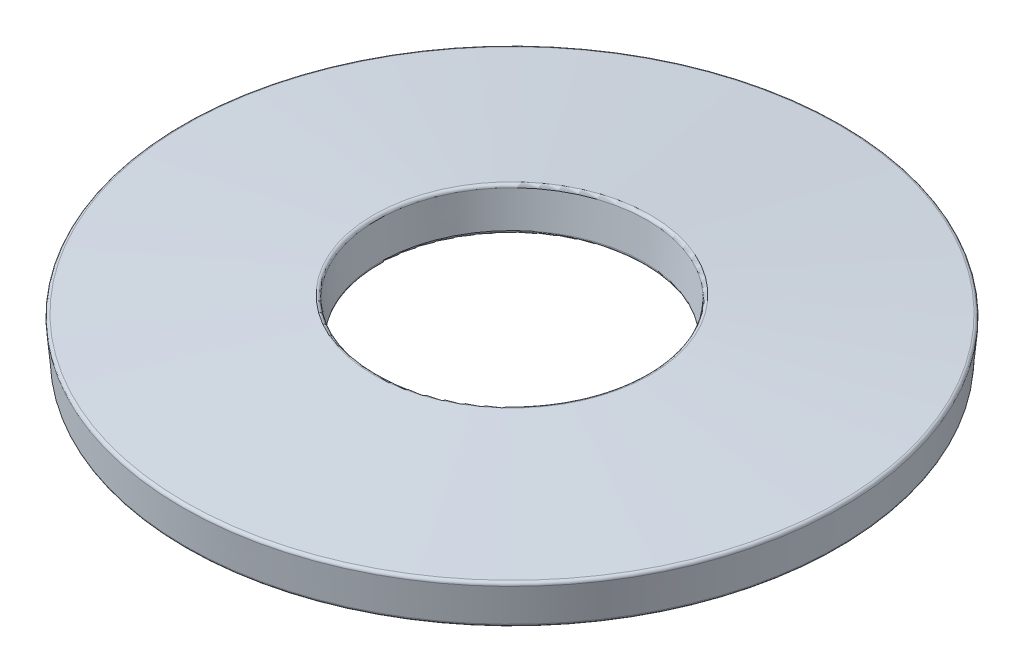
SolidWorks part; units mm, degrees
ref_plane "Front Plane" through (0, 0, 0) normal (0, 0, 1) x (1, 0, 0)
ref_plane "Top Plane" through (0, 0, 0) normal (0, 1, 0) x (1, 0, 0)
ref_plane "Right Plane" through (0, 0, 0) normal (1, 0, 0) x (0, 0, -1)
sketch "Sketch1" plane through (0, 0, 0) normal (0, 0, 1) x (1, 0, 0)
  line L0 (0, 0.35) -> (0, -0.35) construction
  line L1 (1.6427, 0.35) -> (4, 0.1482)
  line L2 (4, 0.1482) -> (3.9573, -0.35)
  line L3 (3.9573, -0.35) -> (1.6, -0.1482)
  line L4 (1.6, -0.1482) -> (1.6427, 0.35)
  line L5 (3.9573, -0.35) -> (1.5919, -0.2999) construction
  line L6 (1.5919, -0.2999) -> (1.6025, 0.2) construction
  line L7 (1.6025, 0.2) -> (3.9679, 0.1499) construction
  line L8 (3.9679, 0.1499) -> (3.9573, -0.35) construction
  line L9 (-3.9679, 0.1499) -> (-3.9573, -0.35) construction
  line L10 (-1.6025, 0.2) -> (-3.9679, 0.1499) construction
  line L11 (-1.5919, -0.2999) -> (-1.6025, 0.2) construction
  line L12 (-3.9573, -0.35) -> (-1.5919, -0.2999) construction
  point P11 (1.6025, 0.2)
  dimension "Thickness" = 0.5
  dimension "OD" = 8
  dimension "ID" = 3.2
  dimension "Height" = 0.7
  dimension "Compressed Height at Working Load" = 0.55
sketch "Sketch3" plane through (0, 0, 0) normal (0, 1, 0) x (1, 0, 0)
  circle A0 centre (0, 0) radius 1.6
  circle A1 centre (0, 0) radius 4
  dimension "D1" = 8
  dimension "D2" = 3.2
sketch "Sketch2" plane through (0, 0, 0) normal (0, 0, 1) x (1, 0, 0)
  line L4 (1.6, -0.1482) -> (1.6427, 0.35) construction
  line L5 (3.9573, -0.35) -> (1.6, -0.1482) construction
  line L6 (4, 0.1482) -> (3.9573, -0.35) construction
  line L7 (1.6427, 0.35) -> (4, 0.1482) construction
  line L8 (1.6, -0.1482) -> (1.6427, 0.35)
  line L9 (3.9573, -0.35) -> (1.6, -0.1482)
  line L10 (4, 0.1482) -> (3.9573, -0.35)
  line L11 (1.6427, 0.35) -> (4, 0.1482)
revolve "Revolve1" add sketch "Sketch2" angle 360 about L0
fillet "Fillet1" radius 0.0375 4 edges at (0, -0.1482, 1.6) (0, -0.35, 3.9573) (0, 0.1482, 4) (0, 0.35, 1.6427)
equation "\"D1@Fillet1\"=\"Thickness@Sketch1\"*0.075"
